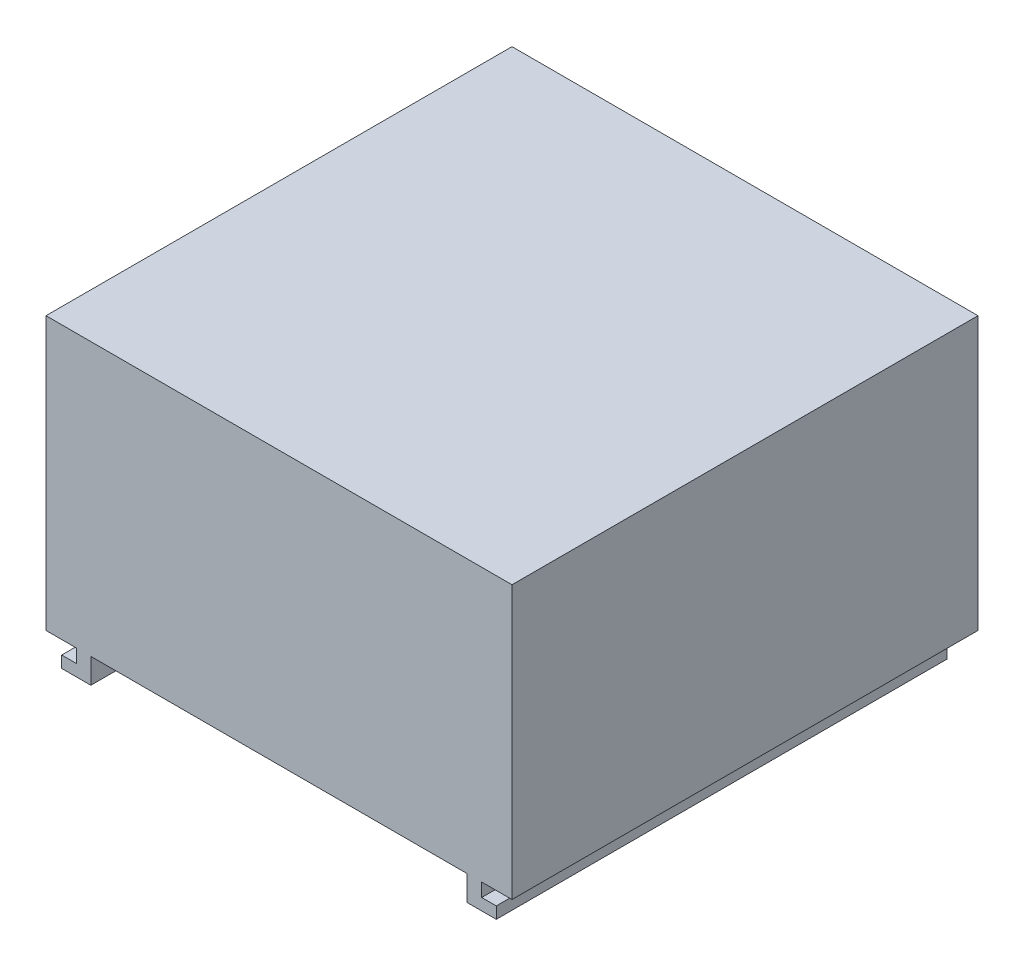
SolidWorks part; units mm, degrees
ref_plane "Front Plane" through (0, 0, 0) normal (0, 0, 1) x (1, 0, 0)
ref_plane "Top Plane" through (0, 0, 0) normal (0, 1, 0) x (1, 0, 0)
ref_plane "Right Plane" through (0, 0, 0) normal (1, 0, 0) x (0, 0, -1)
sketch "Sketch1" plane through (0, 0, 0) normal (0, 1, 0) x (1, 0, 0)
  line L1 (-40, -40) -> (40, -40)
  line L2 (-40, -40) -> (-40, 40)
  line L3 (-40, 40) -> (40, 40)
  line L4 (40, -40) -> (40, 40)
  line L5 (-40, -40) -> (40, 40) construction
  line L6 (-40, 40) -> (40, -40) construction
  point P0 (0, 0)
  dimension "D1" = 80
extrude "Boss-Extrude3" add sketch "Sketch1" against normal blind 2
sketch "Sketch3" plane through (0, 0, 40) normal (0, 0, 1) x (1, 0, 0)
  line L0 (-34.8, -2) -> (-32.3, -2)
  line L1 (-40, -2) -> (40, -2) construction
  line L2 (-32.3, -2) -> (-32.3, -6.3)
  line L3 (-32.3, -6.3) -> (-37.3, -6.3)
  line L4 (-37.3, -6.3) -> (-37.3, -4.3)
  line L5 (-37.3, -4.3) -> (-34.8, -4.3)
  line L6 (-34.8, -4.3) -> (-34.8, -2)
  line L8 (-40, -2) -> (-40, 0) construction
  line L9 (0, 0) -> (0, -6.3)
  line L10 (-40, 0) -> (40, 0) construction
  line L11 (37.3, -4.3) -> (34.8, -4.3)
  line L12 (37.3, -6.3) -> (37.3, -4.3)
  line L13 (32.3, -6.3) -> (37.3, -6.3)
  line L14 (32.3, -2) -> (32.3, -6.3)
  line L15 (34.8, -2) -> (32.3, -2)
  line L16 (34.8, -4.3) -> (34.8, -2)
  point P4 (-37.3, -5.3)
  line M10 (-40, -2) -> (40, -2)
  dimension "D1" = 2.5
  dimension "D2" = 2.7
  dimension "D3" = 2.3
  dimension "D4" = 2
  dimension "D5" = 2.5
extrude "Boss-Extrude5" add sketch "Sketch3" against normal offset from surface (77.35 mm away) 2.65 contours L6 L5 L4 L3 L2 M10 | L13 L12 L11 L16 L15 L14 up to face at (0, -1, -40)
sketch "Sketch5" plane through (0, 0, 0) normal (0, 1, 0) x (1, 0, 0)
  line L12 (-40, -40) -> (40, -40)
  line L13 (-40, -40) -> (-40, 40)
  line L14 (-40, 40) -> (40, 40)
  line L15 (-38.5, -38.5) -> (38.5, -38.5)
  line L16 (38.5, -38.5) -> (38.5, 38.5)
  line L17 (38.5, 38.5) -> (-38.5, 38.5)
  line L18 (-38.5, 38.5) -> (-38.5, -38.5)
  line L19 (-38.5, -38.5) -> (38.5, -38.5)
  line L20 (38.5, -38.5) -> (38.5, 38.5)
  line L21 (38.5, 38.5) -> (-38.5, 38.5)
  line L22 (-38.5, 38.5) -> (-38.5, -38.5)
  line L23 (40, -40) -> (40, 40)
  line L24 (-40, -40) -> (40, 40) construction
  line L25 (-40, 40) -> (40, -40) construction
  point P0 (0, 0)
  dimension "D1" = 1.5
sketch "Sketch7" plane through (0, 0, 0) normal (0, 1, 0) x (1, 0, 0)
  line L15 (-40, -40) -> (-40, 40) construction
  line L16 (-32.3, 38.5) -> (32.3, 38.5)
  line L17 (-32.3, 38.5) -> (-32.3, -38.5)
  line L18 (-32.3, -38.5) -> (32.3, -38.5)
  line L19 (32.3, 38.5) -> (32.3, -38.5)
  line L20 (-32.3, 38.5) -> (32.3, -38.5) construction
  line L21 (-32.3, -38.5) -> (32.3, 38.5) construction
  line L23 (-40, -40) -> (40, -40) construction
  point P13 (0, 0)
  dimension "D1" = 7.7
  dimension "D2" = 1.5
extrude "Cut-Extrude1" cut sketch "Sketch7" against normal up to next
extrude "Boss-Extrude6" add sketch "Sketch5" along normal blind 44.8
sketch "Sketch8" plane through (0, 44.8, 0) normal (0, 1, 0) x (1, 0, 0)
  line L1 (-40, 40) -> (40, 40)
  line L2 (-40, 40) -> (-40, -40)
  line L3 (-40, -40) -> (40, -40)
  line L4 (40, 40) -> (40, -40)
  line L5 (-40, 40) -> (40, -40) construction
  line L6 (-40, -40) -> (40, 40) construction
  point P0 (0, 0)
extrude "Boss-Extrude7" add sketch "Sketch8" against normal blind 1.5
